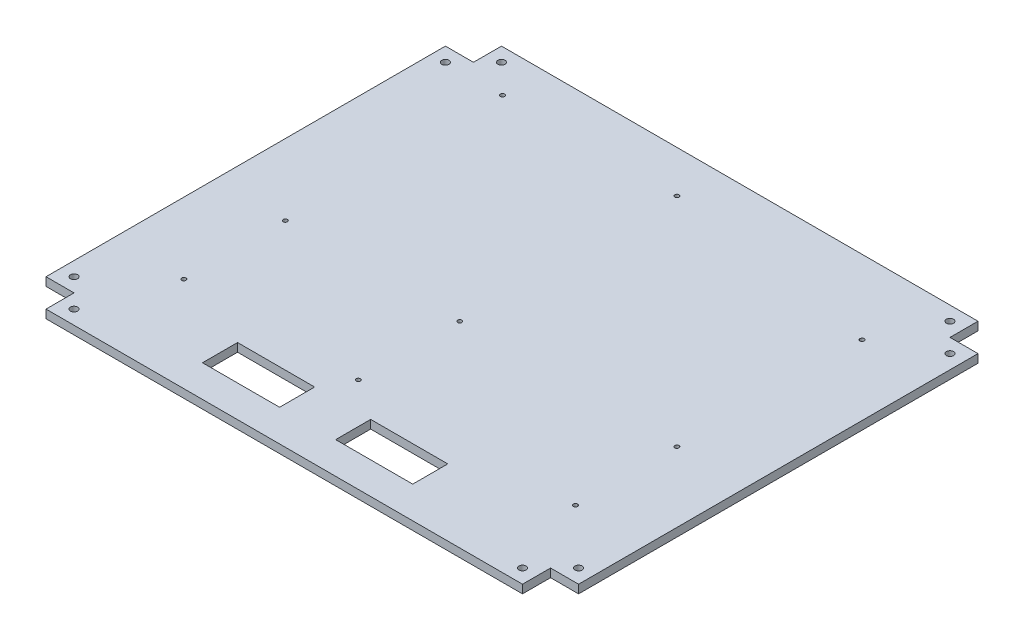
SolidWorks part; units mm, degrees
ref_plane "Front" through (0, 0, 0) normal (0, 0, 1) x (1, 0, 0)
ref_plane "Top" through (0, 0, 0) normal (0, 1, 0) x (1, 0, 0)
ref_plane "Right" through (0, 0, 0) normal (1, 0, 0) x (0, 0, -1)
sketch "Base Plate" plane through (0, 0, 0) normal (0, 1, 0) x (1, 0, 0)
  line L0 (-190, 162.5) -> (190, -162.5) construction
  line L1 (-190, 162.5) -> (190, 162.5)
  line L2 (-190, 162.5) -> (-190, -162.5)
  line L3 (-190, -162.5) -> (190, -162.5)
  line L4 (190, 162.5) -> (190, -162.5)
  line L5 (149, 162.5) -> (149, -162.5) construction
  line L6 (-155.8, 162.5) -> (-155.8, -162.5) construction
  line L7 (-155.8, -81.34) -> (149, -81.34) construction
  line L8 (-139.29, 162.5) -> (-139.29, -81.34) construction
  line L9 (14, -114.83) -> (69, -114.83)
  line L10 (14, -114.83) -> (14, -139.83)
  line L11 (14, -139.83) -> (69, -139.83)
  line L12 (69, -114.83) -> (69, -139.83)
  line L13 (-26, -114.83) -> (-81, -114.83)
  line L14 (-26, -114.83) -> (-26, -139.83)
  line L15 (-26, -139.83) -> (-81, -139.83)
  line L16 (-81, -114.83) -> (-81, -139.83)
  line L17 (-155.8, -94.83) -> (149, -94.83) construction
  line L18 (-155.8, 132.5) -> (149, 132.5) construction
  line L19 (-155.8, -22.44) -> (149, -22.44) construction
  line L20 (-14.83, 162.5) -> (-14.83, -81.34) construction
  line L21 (140.11, 162.5) -> (140.11, -81.34) construction
  circle A0 centre (-139.29, -94.83) radius 1.5
  circle A3 centre (-14.83, -22.44) radius 1.5
  circle A4 centre (-139.29, -22.44) radius 1.5
  circle A5 centre (-139.29, 132.5) radius 1.5
  circle A6 centre (-14.83, 132.5) radius 1.5
  circle A7 centre (-14.83, -94.83) radius 1.5
  circle A8 centre (140.11, -94.83) radius 1.5
  circle A9 centre (140.11, -22.44) radius 1.5
  circle A10 centre (140.11, 109.64) radius 1.5
  circle A11 centre (-180, -152.5) radius 2.5
  circle A12 centre (180, -152.5) radius 2.5
  circle A13 centre (-180, 152.5) radius 2.5
  circle A14 centre (180, 152.5) radius 2.5
  point P53 (149, -81.34)
  dimension "D14" = 3
  dimension "D15" = 30
  dimension "D22" = 5
  dimension "D1" = 325
  dimension "D2" = 380
  dimension "D3" = 41
  dimension "D4" = 304.8
  dimension "D5" = 154.94
  dimension "D6" = 243.84
  dimension "D7" = 80
  dimension "D8" = 55
  dimension "D9" = 25
  dimension "D10" = 20
  dimension "D11" = 40
  dimension "D12" = 55
  dimension "D13" = 16.51
  dimension "D16" = 279.4
  dimension "D17" = 227.33
  dimension "D18" = 124.46
  dimension "D19" = 22.86
  dimension "D20" = 10
  dimension "D21" = 10
  dimension "D23" = 10
  dimension "D24" = 10
  dimension "D25" = 10
  dimension "D26" = 10
  dimension "D27" = 10
  dimension "D28" = 10
  dimension "D29" = 20
  dimension "D30" = 25
extrude "Boss-Extrude1" add sketch "Base Plate" along normal blind 6
sketch "Sketch1" plane through (0, 6, 0) normal (0, 1, 0) x (1, 0, 0)
  line L1 (-190, 162.5) -> (-170, 162.5)
  line L2 (-190, 162.5) -> (-190, 142.5)
  line L3 (-190, 142.5) -> (-170, 142.5)
  line L4 (-170, 162.5) -> (-170, 142.5)
  line L5 (190, 162.5) -> (170, 162.5)
  line L6 (190, 162.5) -> (190, 142.5)
  line L7 (190, 142.5) -> (170, 142.5)
  line L8 (170, 162.5) -> (170, 142.5)
  line L9 (190, -162.5) -> (170, -162.5)
  line L10 (190, -162.5) -> (190, -142.5)
  line L11 (190, -142.5) -> (170, -142.5)
  line L12 (170, -162.5) -> (170, -142.5)
  line L13 (-190, -162.5) -> (-170, -162.5)
  line L14 (-190, -162.5) -> (-190, -142.5)
  line L15 (-190, -142.5) -> (-170, -142.5)
  line L16 (-170, -162.5) -> (-170, -142.5)
  dimension "D1" = 20
  dimension "D2" = 20
  dimension "D3" = 20
  dimension "D4" = 20
extrude "Cut-Extrude1" cut sketch "Sketch1" against normal blind 10
sketch "Sketch2" plane through (0, 0, 0) normal (0, -1, 0) x (1, 0, 0)
  line L0 (-170, 162.5) -> (-170, 142.5) construction
  line L1 (-170, 142.5) -> (-190, 142.5) construction
  line L2 (-190, -142.5) -> (-170, -142.5) construction
  line L4 (170, -162.5) -> (-170, -162.5) construction
  line L5 (190, 142.5) -> (190, -142.5) construction
  line L6 (170, -162.5) -> (170, -142.5) construction
  circle A0 centre (-160, 152.5) radius 2.55
  circle A1 centre (-180, 132.5) radius 2.55
  circle A2 centre (-180, -132.5) radius 2.55
  circle A3 centre (-160, -152.5) radius 2.55
  circle A4 centre (160, -152.5) radius 2.55
  circle A5 centre (180, -132.5) radius 2.55
  circle A6 centre (180, 132.5) radius 2.55
  circle A7 centre (160, 152.5) radius 2.55
  point P8 (-180, 142.5)
  point P10 (-170, 152.5)
  dimension "D1" = 5.1
  dimension "D2" = 5.1
  dimension "D5" = 5.1
  dimension "D7" = 5.1
  dimension "D9" = 5.1
  dimension "D10" = 5.1
  dimension "D13" = 5.1
  dimension "D14" = 5.1
  dimension "D3" = 10
  dimension "D4" = 10
  dimension "D6" = 10
  dimension "D8" = 10
  dimension "D11" = 10
  dimension "D12" = 10
extrude "Cut-Extrude2" cut sketch "Sketch2" against normal blind 10
